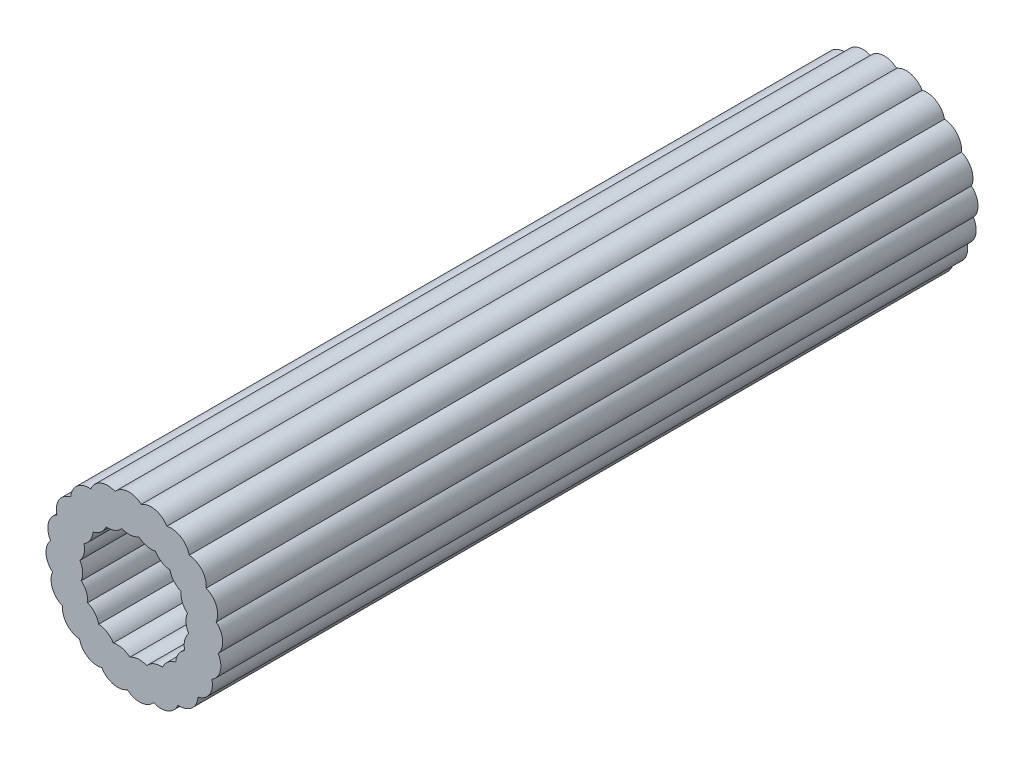
SolidWorks part; units mm, degrees
ref_plane "前视基准面" through (0, 0, 0) normal (0, 0, 1) x (1, 0, 0)
ref_plane "上视基准面" through (0, 0, 0) normal (0, 1, 0) x (1, 0, 0)
ref_plane "右视基准面" through (0, 0, 0) normal (1, 0, 0) x (0, 0, -1)
sketch "草图1" plane through (0, 0, 0) normal (0, 0, 1) x (1, 0, 0)
  arc A0 (-16.7846, 71.2691) -> (-37.9864, 62.5943) centre (-23.1549, 56.5919) ccw
  arc A1 (-10.9041, 46.3002) -> (3.9371, 47.4037) centre (-4.5338, 60.9774) ccw
  arc A2 (3.9371, 47.4037) -> (18.3929, 43.867) centre (14.5312, 59.394) ccw
  arc A3 (18.3929, 43.867) -> (31.0484, 36.0362) centre (32.1737, 51.9966) ccw
  arc A4 (31.0484, 36.0362) -> (40.6646, 24.678) centre (46.6669, 39.5095) ccw
  arc A5 (40.6646, 24.678) -> (46.3002, 10.9041) centre (56.5919, 23.1549) ccw
  arc A6 (46.3002, 10.9041) -> (47.4037, -3.9371) centre (60.9774, 4.5338) ccw
  arc A7 (47.4037, -3.9371) -> (43.867, -18.3929) centre (59.394, -14.5312) ccw
  arc A8 (43.867, -18.3929) -> (36.0362, -31.0484) centre (51.9966, -32.1737) ccw
  arc A9 (36.0362, -31.0484) -> (24.678, -40.6646) centre (39.5095, -46.6669) ccw
  arc A10 (24.678, -40.6646) -> (10.9041, -46.3002) centre (23.1549, -56.5919) ccw
  arc A11 (10.9041, -46.3002) -> (-3.9371, -47.4037) centre (4.5338, -60.9774) ccw
  arc A12 (-3.9371, -47.4037) -> (-18.3929, -43.867) centre (-14.5312, -59.394) ccw
  arc A13 (-18.3929, -43.867) -> (-31.0484, -36.0362) centre (-32.1737, -51.9966) ccw
  arc A14 (-31.0484, -36.0362) -> (-40.6646, -24.678) centre (-46.6669, -39.5095) ccw
  arc A15 (-40.6646, -24.678) -> (-46.3002, -10.9041) centre (-56.5919, -23.1549) ccw
  arc A16 (-46.3002, -10.9041) -> (-47.4037, 3.9371) centre (-60.9774, -4.5338) ccw
  arc A17 (-47.4037, 3.9371) -> (-43.867, 18.3929) centre (-59.394, 14.5312) ccw
  arc A18 (-43.867, 18.3929) -> (-36.0362, 31.0484) centre (-51.9966, 32.1737) ccw
  arc A19 (-36.0362, 31.0484) -> (-24.678, 40.6646) centre (-39.5095, 46.6669) ccw
  arc A20 (6.0603, 72.9677) -> (-16.7846, 71.2691) centre (-4.5338, 60.9774) ccw
  arc A21 (28.312, 67.5237) -> (6.0603, 72.9677) centre (14.5312, 59.394) ccw
  arc A22 (47.7922, 55.4699) -> (28.312, 67.5237) centre (32.1737, 51.9966) ccw
  arc A23 (62.5943, 37.9864) -> (47.7922, 55.4699) centre (46.6669, 39.5095) ccw
  arc A24 (71.2691, 16.7846) -> (62.5943, 37.9864) centre (56.5919, 23.1549) ccw
  arc A25 (72.9677, -6.0603) -> (71.2691, 16.7846) centre (60.9774, 4.5338) ccw
  arc A26 (67.5237, -28.312) -> (72.9677, -6.0603) centre (59.394, -14.5312) ccw
  arc A27 (55.4699, -47.7922) -> (67.5237, -28.312) centre (51.9966, -32.1737) ccw
  arc A28 (37.9864, -62.5943) -> (55.4699, -47.7922) centre (39.5095, -46.6669) ccw
  arc A29 (16.7846, -71.2691) -> (37.9864, -62.5943) centre (23.1549, -56.5919) ccw
  arc A30 (-6.0603, -72.9677) -> (16.7846, -71.2691) centre (4.5338, -60.9774) ccw
  arc A31 (-28.312, -67.5237) -> (-6.0603, -72.9677) centre (-14.5312, -59.394) ccw
  arc A32 (-47.7922, -55.4699) -> (-28.312, -67.5237) centre (-32.1737, -51.9966) ccw
  arc A33 (-62.5943, -37.9864) -> (-47.7922, -55.4699) centre (-46.6669, -39.5095) ccw
  arc A34 (-71.2691, -16.7846) -> (-62.5943, -37.9864) centre (-56.5919, -23.1549) ccw
  arc A35 (-72.9677, 6.0603) -> (-71.2691, -16.7846) centre (-60.9774, -4.5338) ccw
  arc A36 (-67.5237, 28.312) -> (-72.9677, 6.0603) centre (-59.394, 14.5312) ccw
  arc A37 (-55.4699, 47.7922) -> (-67.5237, 28.312) centre (-51.9966, 32.1737) ccw
  arc A38 (-24.678, 40.6646) -> (-10.9041, 46.3002) centre (-23.1549, 56.5919) ccw
  arc A39 (-37.9864, 62.5943) -> (-55.4699, 47.7922) centre (-39.5095, 46.6669) ccw
  point P43 (0, 0)
  dimension "D1" = 20
extrude "凸台-拉伸1" add sketch "草图1" along normal blind 658.1032
